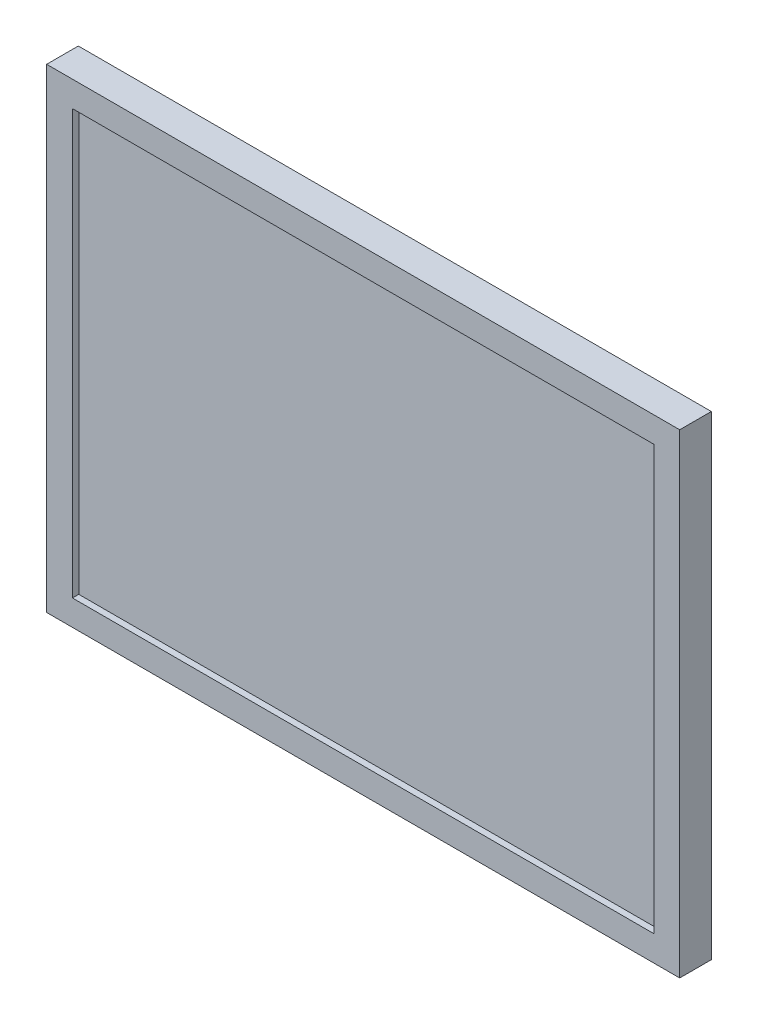
SolidWorks part; units mm, degrees
ref_plane "Front Plane" through (0, 0, 0) normal (0, 0, 1) x (1, 0, 0)
ref_plane "Top Plane" through (0, 0, 0) normal (0, 1, 0) x (1, 0, 0)
ref_plane "Right Plane" through (0, 0, 0) normal (1, 0, 0) x (0, 0, -1)
sketch "Sketch1" plane through (0, 0, 0) normal (0, 0, 1) x (1, 0, 0)
  line L1 (100, -75) -> (-100, -75)
  line L2 (100, -75) -> (100, 75)
  line L3 (100, 75) -> (-100, 75)
  line L4 (-100, -75) -> (-100, 75)
  line L5 (100, -75) -> (-100, 75) construction
  line L6 (100, 75) -> (-100, -75) construction
  point P0 (0, 0)
  dimension "D1" = 200
  dimension "D2" = 150
extrude "Boss-Extrude1" add sketch "Sketch1" along normal blind 10
sketch "Sketch2" plane through (0, 0, 10) normal (0, 0, 1) x (1, 0, 0)
  line L1 (91.8514, -66.9528) -> (-91.8514, -66.9528)
  line L2 (91.8514, -66.9528) -> (91.8514, 66.9528)
  line L3 (91.8514, 66.9528) -> (-91.8514, 66.9528)
  line L4 (-91.8514, -66.9528) -> (-91.8514, 66.9528)
  line L5 (91.8514, -66.9528) -> (-91.8514, 66.9528) construction
  line L6 (91.8514, 66.9528) -> (-91.8514, -66.9528) construction
  point P0 (0, 0)
extrude "Cut-Extrude1" cut sketch "Sketch2" against normal blind 2
